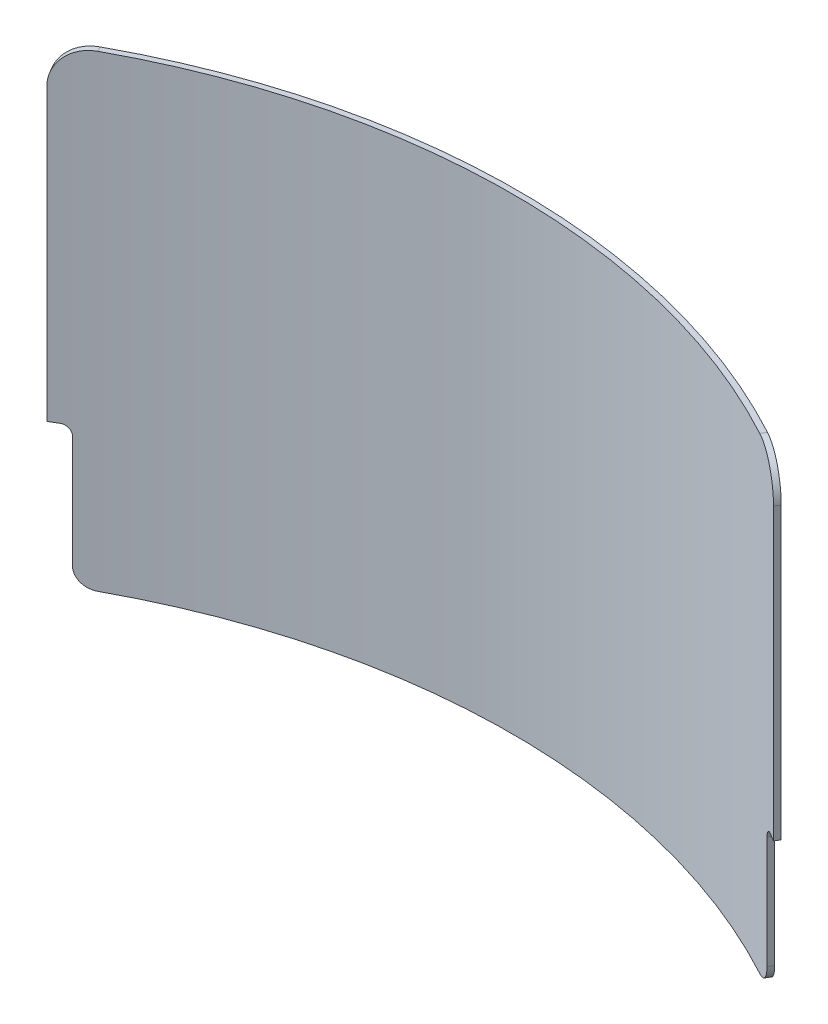
SolidWorks part; units mm, degrees
material "AISI 1020"
ref_plane "Plano frontal" through (0, 0, 0) normal (0, 0, 1) x (1, 0, 0)
ref_plane "Plano superior" through (0, 0, 0) normal (0, 1, 0) x (1, 0, 0)
ref_plane "Plano direito" through (0, 0, 0) normal (1, 0, 0) x (0, 0, -1)
sketch "Esboço2" plane through (0, 0, 0) normal (0, 1, 0) x (1, 0, 0)
  arc A0 (-195, -55) -> (195, -55) centre (0, -373.1818) cw
  dimension "D1" = 390
  dimension "D2" = 55
  dimension "D3" = 195
extrude "Extrusão-Fina1" add sketch "Esboço2" along normal mid plane 250 thin thin type mid plane wall 3
sketch "Esboço3" plane through (166.2607, 0, 101.894) normal (0.8526, 0, 0.5225) x (0.5225, 0, -0.8526)
  line L0 (53.5, 125) -> (53.5, -125) construction
  line L1 (60.5, -50) -> (50.5, -50)
  line L2 (60.5, -50) -> (60.5, -125)
  line L3 (60.5, -125) -> (50.5, -125)
  line L4 (50.5, -50) -> (50.5, -125)
  line L6 (56.5, -125) -> (53.5, -125) construction
  dimension "D1" = 10
  dimension "D2" = 3
  dimension "D3" = 75
extrude "Corte-extrusão1" cut sketch "Esboço3" against normal blind 10
fillet "Filete5" radius 5 1 edges at (186.4038, -50, 49.8889)
fillet "Filete6" radius 20 2 edges at (195, 125, 55) (-195, 125, 55)
mirror "Espelhar6" about plane through (0, 0, 0) normal (1, 0, 0) of "Filete5", "Corte-extrusão1"
fillet "Filete8" radius 10 2 edges at (186.4038, -125, 49.8889) (-186.4038, -125, 49.8889)
